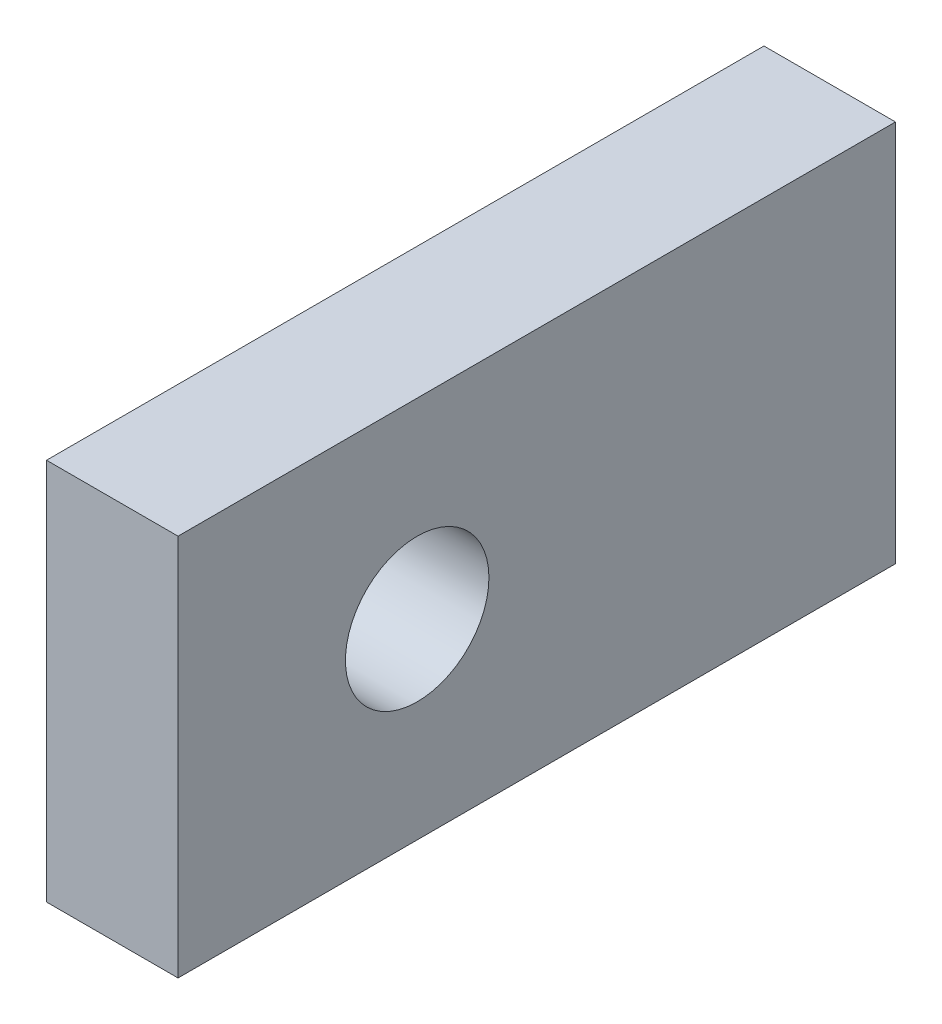
SolidWorks part; units mm, degrees
ref_plane "前视基准面" through (0, 0, 0) normal (0, 0, 1) x (1, 0, 0)
ref_plane "上视基准面" through (0, 0, 0) normal (0, 1, 0) x (1, 0, 0)
ref_plane "右视基准面" through (0, 0, 0) normal (1, 0, 0) x (0, 0, -1)
sketch "草图1" plane through (0, 0, 0) normal (1, 0, 0) x (0, 0, -1)
  line L1 (7.5, -4) -> (-7.5, -4)
  line L2 (7.5, -4) -> (7.5, 4)
  line L3 (7.5, 4) -> (-7.5, 4)
  line L4 (-7.5, -4) -> (-7.5, 4)
  line L5 (7.5, -4) -> (-7.5, 4) construction
  line L6 (7.5, 4) -> (-7.5, -4) construction
  point P0 (0, 0)
  dimension "D1" = 15
  dimension "D2" = 8
extrude "凸台-拉伸1" add sketch "草图1" along normal blind 3.25
sketch "草图2" plane through (3.25, 0, 0) normal (1, 0, 0) x (0, 0, -1)
  line L0 (7.5, 0) -> (-7.5, 0) construction
  line L1 (7.5, -4) -> (7.5, 4) construction
  line L2 (-7.5, 4) -> (-7.5, -4) construction
  circle A0 centre (-2.5, 0) radius 1.5
  point P10 (-7.3031, 0)
  dimension "D1" = 3
  dimension "D2" = 10
extrude "切除-拉伸1" cut sketch "草图2" against normal through all
chamfer "倒角1" distance 0.5 angle 45 4 edges at (0, -4, 0) (0, 0, -7.5) (0, 4, 0) (0, 0, 7.5)
